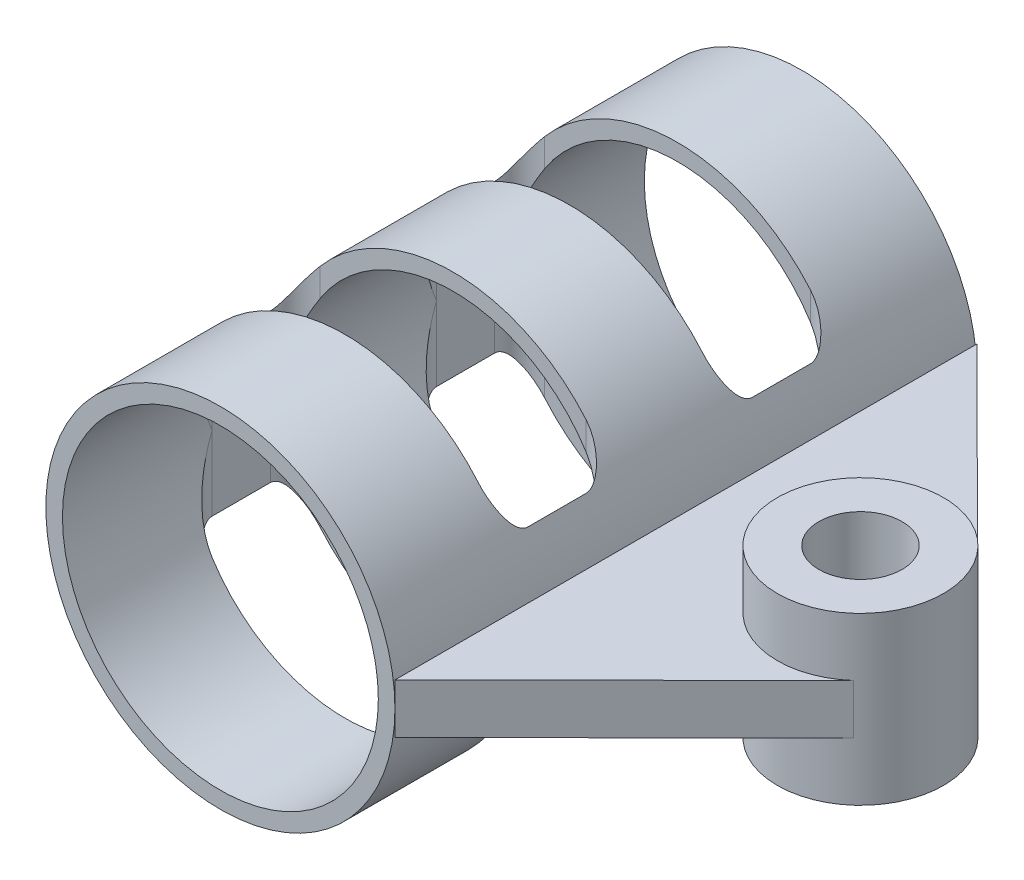
SolidWorks part; units mm, degrees
ref_plane "Front Plane" through (0, 0, 0) normal (0, 0, 1) x (1, 0, 0)
ref_plane "Top Plane" through (0, 0, 0) normal (0, 1, 0) x (1, 0, 0)
ref_plane "Right Plane" through (0, 0, 0) normal (1, 0, 0) x (0, 0, -1)
sketch "Sketch1" plane through (0, 0, 0) normal (0, 0, 1) x (1, 0, 0)
  circle A0 centre (0, 0) radius 19
  circle A1 centre (0, 0) radius 21
  dimension "D1" = 38
  dimension "D2" = 42
extrude "Boss-Extrude1" add sketch "Sketch1" along normal blind 70
sketch "Sketch2" plane through (0, 0, 0) normal (0, 1, 0) x (1, 0, 0)
  circle A0 centre (42, -35) radius 10
  dimension "D2" = 20
extrude "Boss-Extrude2" add sketch "Sketch2" along normal mid plane 20 separate body
sketch "Sketch3" plane through (0, 10, 0) normal (0, 1, 0) x (1, 0, 0)
  circle A0 centre (42, -35) radius 5
  dimension "D1" = 10
extrude "Cut-Extrude1" cut sketch "Sketch3" against normal blind 20
sketch "Sketch4" plane through (0, 0, 0) normal (0, 1, 0) x (1, 0, 0)
  line L0 (21, 0) -> (48.6348, -27.518)
  line L1 (21, 0) -> (21, -70)
  line L2 (21, -70) -> (48.6348, -42.482)
  circle A0 centre (42, -35) radius 10 construction
  arc A1 (48.6348, -27.518) -> (48.6348, -42.482) centre (42, -35) ccw
extrude "Boss-Extrude3" add sketch "Sketch4" along normal mid plane 6
sketch "Sketch5" plane through (0, 0, 0) normal (0, 1, 0) x (1, 0, 0)
  line L1 (-16, -15) -> (16, -15)
  line L2 (-19, -18) -> (-19, -25)
  line L3 (-16, -28) -> (16, -28)
  line L4 (19, -18) -> (19, -25)
  line L9 (19, -52) -> (19, -45)
  line L10 (-16, -42) -> (16, -42)
  line L11 (-19, -52) -> (-19, -45)
  line L12 (-16, -55) -> (16, -55)
  arc A0 (16, -15) -> (19, -18) centre (16, -18) cw
  arc A1 (16, -28) -> (19, -25) centre (16, -25) ccw
  arc A2 (-19, -25) -> (-16, -28) centre (-16, -25) ccw
  arc A3 (-16, -15) -> (-19, -18) centre (-16, -18) ccw
  arc A4 (-16, -55) -> (-19, -52) centre (-16, -52) cw
  arc A5 (-19, -45) -> (-16, -42) centre (-16, -45) cw
  arc A6 (16, -42) -> (19, -45) centre (16, -45) cw
  arc A7 (16, -55) -> (19, -52) centre (16, -52) ccw
  point P0 (0, -21.5)
  point P37 (0, -48.5)
  dimension "D4" = 3
extrude "Cut-Extrude2" cut sketch "Sketch5" against normal mid plane 50
